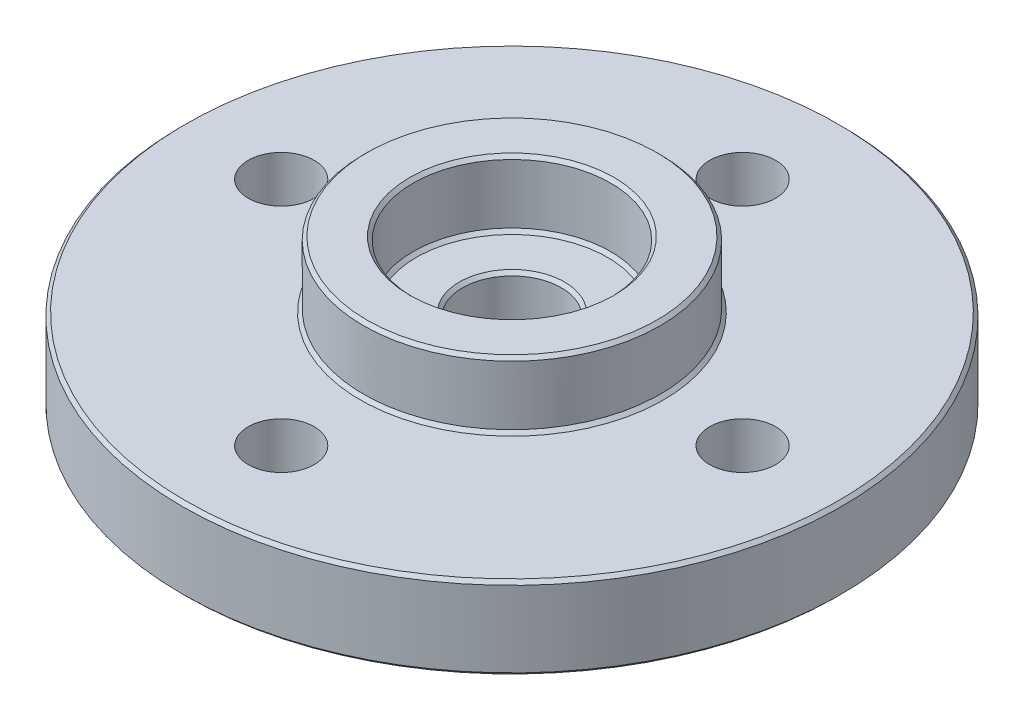
SolidWorks part; units mm, degrees
ref_plane "前视基准面" through (0, 0, 0) normal (0, 0, 1) x (1, 0, 0)
ref_plane "上视基准面" through (0, 0, 0) normal (0, 1, 0) x (1, 0, 0)
ref_plane "右视基准面" through (0, 0, 0) normal (1, 0, 0) x (0, 0, -1)
other "Configuration Table"
sketch "草图1" plane through (0, 0, 0) normal (0, 1, 0) x (1, 0, 0)
  line L0 (-10, 0) -> (10, 0) construction
  line L1 (0, 10) -> (0, -10) construction
  circle A0 centre (0, 0) radius 10
  circle A1 centre (0, 0) radius 1.5
  circle A2 centre (0, 0) radius 7 construction
  circle A3 centre (0, 7) radius 1
  circle A4 centre (7, 0) radius 1
  circle A5 centre (0, -7) radius 1
  circle A6 centre (-7, 0) radius 1
  point P20 (0, 0)
  dimension "D1" = 20
  dimension "D2" = 3
  dimension "D3" = 14
  dimension "D5" = 2
  dimension "D4" = 4
extrude "凸台-拉伸1" add sketch "草图1" along normal blind 2.5
sketch "草图2" plane through (0, 2.5, 0) normal (0, 1, 0) x (1, 0, 0)
  circle A0 centre (0, 0) radius 3
  circle A1 centre (0, 0) radius 4.5
  dimension "D1" = 9
  dimension "D2" = 6
extrude "凸台-拉伸2" add sketch "草图2" along normal blind 2
chamfer "倒角1" distance 0.1 angle 45 1 edges at (0, 4.5, 4.5)
chamfer "倒角2" distance 0.1 angle 45 6 edges at (0, 0, 10) (0, 2.5, 10) (0, 2.5, 4.5) (0, 2.5, 1.5) (0, 2.5, 3) (0, 4.5, 3)
